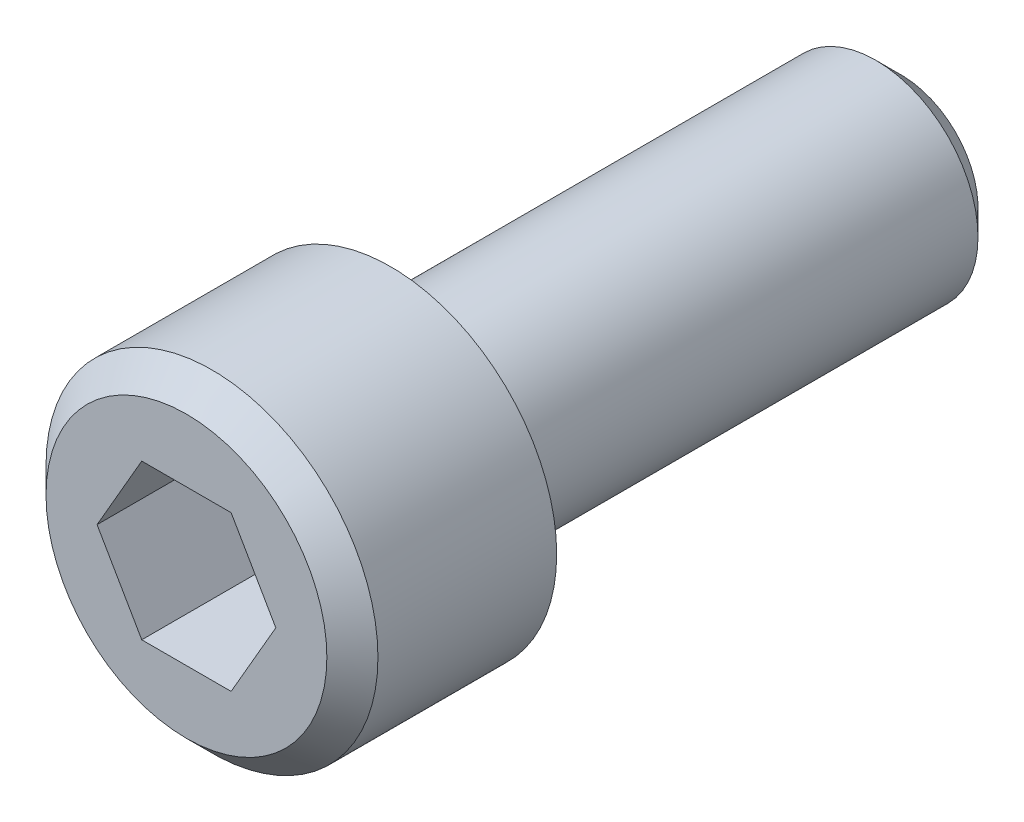
SolidWorks part; units mm, degrees
ref_plane "Alzado" through (0, 0, 0) normal (0, 0, 1) x (1, 0, 0)
ref_plane "Planta" through (0, 0, 0) normal (0, 1, 0) x (1, 0, 0)
ref_plane "Vista lateral" through (0, 0, 0) normal (1, 0, 0) x (0, 0, -1)
sketch "Croquis1" plane through (0, 0, 0) normal (0, 0, 1) x (1, 0, 0)
  circle A0 centre (0, 0) radius 6.5
  dimension "D1" = 13
extrude "Saliente-Extruir1" add sketch "Croquis1" along normal blind 8
sketch "Croquis2" plane through (0, 0, 0) normal (0, 0, -1) x (-1, 0, 0)
  circle A0 centre (0, 0) radius 4
  dimension "D1" = 8
extrude "Saliente-Extruir2" add sketch "Croquis2" along normal blind 20
chamfer "Chaflán1" distance 1 angle 45 2 edges at (6.5, 0, 8) (-4, 0, -20)
sketch "Croquis3" plane through (0, 0, 8) normal (0, 0, 1) x (1, 0, 0)
  line L1 (3.5, 0) -> (1.75, 3.0311)
  line L2 (1.75, 3.0311) -> (-1.75, 3.0311)
  line L3 (-1.75, 3.0311) -> (-3.5, 0)
  line L4 (-3.5, 0) -> (-1.75, -3.0311)
  line L5 (-1.75, -3.0311) -> (1.75, -3.0311)
  line L6 (1.75, -3.0311) -> (3.5, 0)
  circle A0 centre (0, 0) radius 3.0311 construction
  dimension "D1" = 7
extrude "Cortar-Extruir1" cut sketch "Croquis3" against normal blind 6
